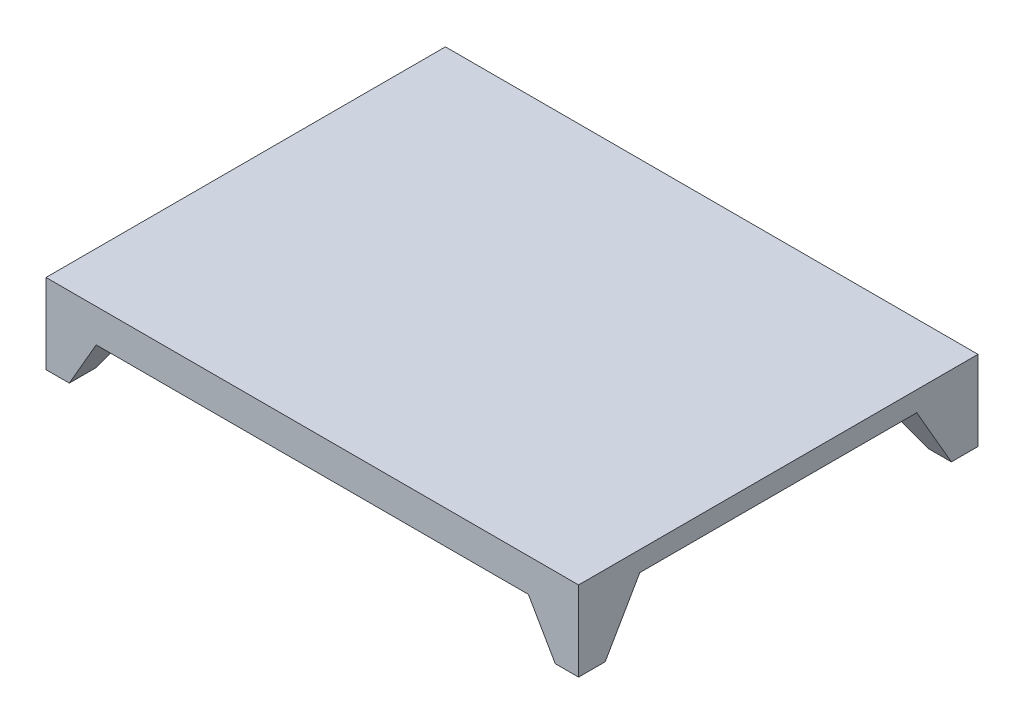
SolidWorks part; units mm, degrees
ref_plane "Alzado" through (0, 0, 0) normal (0, 0, 1) x (1, 0, 0)
ref_plane "Planta" through (0, 0, 0) normal (0, 1, 0) x (1, 0, 0)
ref_plane "Vista lateral" through (0, 0, 0) normal (1, 0, 0) x (0, 0, -1)
sketch "Croquis1" plane through (0, 0, 0) normal (0, 0, 1) x (1, 0, 0)
  line L1 (-400, -60) -> (400, -60)
  line L2 (-400, -60) -> (-400, 60)
  line L3 (-400, 60) -> (400, 60)
  line L4 (400, -60) -> (400, 60)
  line L5 (-400, -60) -> (400, 60) construction
  line L6 (-400, 60) -> (400, -60) construction
  point P0 (0, 0)
  dimension "D1" = 800
  dimension "D2" = 120
extrude "Saliente-Extruir1" add sketch "Croquis1" along normal mid plane 600
sketch "Croquis2" plane through (400, 0, 0) normal (1, 0, 0) x (0, 0, -1)
  line L0 (-260, -60) -> (-208.0385, 30)
  line L1 (-300, -60) -> (300, -60) construction
  line L2 (-208.0385, 30) -> (208.0385, 30)
  line L3 (0, 30) -> (0, -60)
  line L4 (260, -60) -> (-260, -60)
  line L5 (-300, 60) -> (300, 60) construction
  line L6 (0, 177.7694) -> (0, -159.5527) construction
  line L7 (260, -60) -> (208.0385, 30)
  point P11 (-211.0619, 30)
  line M9 (-300, -60) -> (300, -60)
  dimension "D1" = 60
  dimension "D2" = 30
  dimension "D3" = 260
extrude "Cortar-Extruir1" cut sketch "Croquis2" against normal through all contours L3 L2 L0 M9 | L7 L2 L3 M9
sketch "Croquis3" plane through (0, 0, 300) normal (0, 0, 1) x (1, 0, 0)
  line L0 (0, 199.3362) -> (0, -158.2964) construction
  line L1 (-365, -60) -> (-324.5855, 10)
  line L2 (-400, -60) -> (400, -60) construction
  line L3 (-324.5855, 10) -> (324.5855, 10)
  line L4 (0, 10) -> (0, -60)
  line L5 (365, -60) -> (-365, -60)
  line L6 (400, 60) -> (-400, 60) construction
  line L7 (365, -60) -> (324.5855, 10)
  line M7 (-400, -60) -> (400, -60)
  dimension "D1" = 60
  dimension "D2" = 365
  dimension "D3" = 50
extrude "Cortar-Extruir2" cut sketch "Croquis3" against normal blind 600 contours L4 L3 L1 M7 | L7 L3 L4 M7
